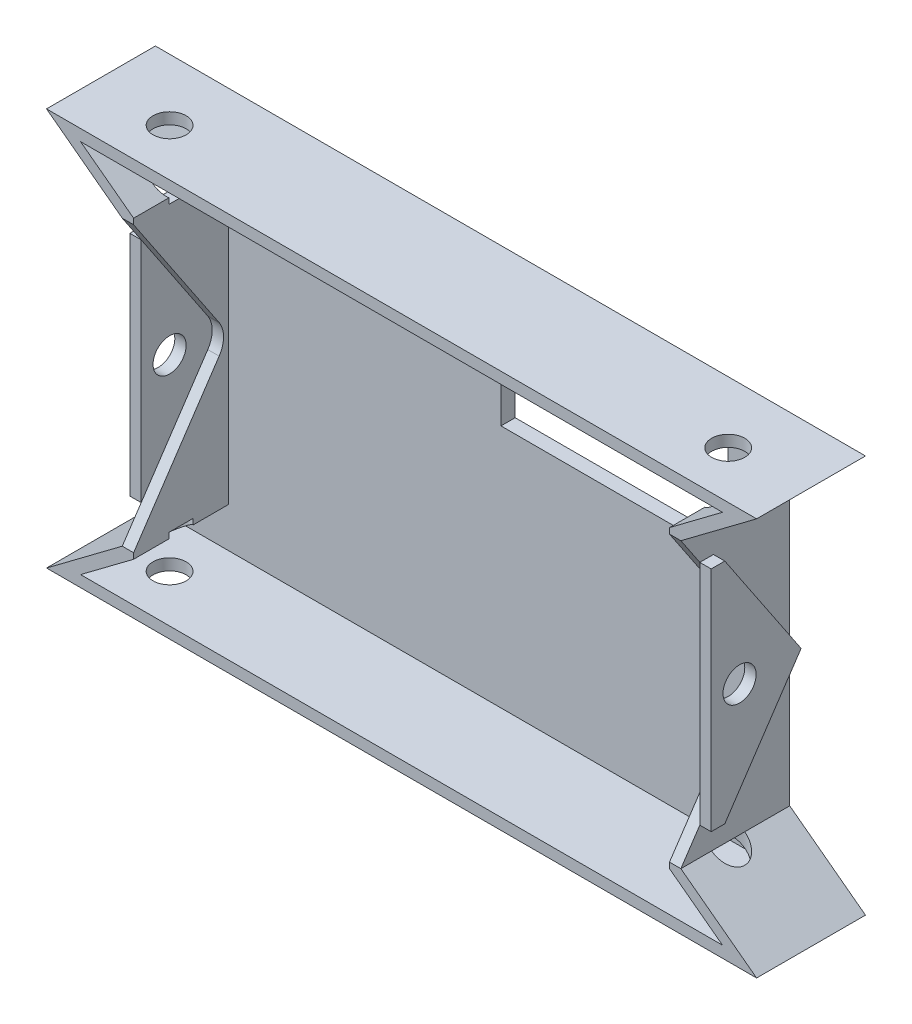
SolidWorks part; units mm, degrees
ref_plane "前视基准面" through (0, 0, 0) normal (0, 0, 1) x (1, 0, 0)
ref_plane "上视基准面" through (0, 0, 0) normal (0, 1, 0) x (1, 0, 0)
ref_plane "右视基准面" through (0, 0, 0) normal (1, 0, 0) x (0, 0, -1)
sketch "草图1" plane through (0, 0, 0) normal (0, 0, 1) x (1, 0, 0)
  line L0 (0, 42) -> (0, 0) construction
  line L5 (29.5, 6) -> (37.5, 0)
  line L6 (37.5, 0) -> (-37.5, 0)
  line L7 (0, 21) -> (25.1808, 21) construction
  line L8 (29.5, 6) -> (29.5, 36)
  line L9 (37.5, 42) -> (-37.5, 42)
  line L10 (29.5, 36) -> (37.5, 42)
  line L11 (-29.5, 36) -> (-37.5, 42)
  line L12 (-29.5, 6) -> (-29.5, 36)
  line L13 (-29.5, 6) -> (-37.5, 0)
  point P2 (29.5, 21)
  point P14 (0, 0)
  point P16 (37.8655, 46.0267)
  point P19 (43.209, 41.009)
  dimension "D1" = 59
  dimension "D2" = 42
  dimension "D3" = 6
  dimension "D4" = 8
extrude "凸台-拉伸1" add sketch "草图1" along normal blind 1.5
sketch "草图2" plane through (0, 0, 1.5) normal (0, 0, 1) x (1, 0, 0)
  line L0 (28.3, 36.6) -> (33.9, 40.8)
  line L1 (33.9, 40.8) -> (-33.9, 40.8)
  line L2 (-33.9, 40.8) -> (-28.3, 36.6)
  line L3 (-28.3, 36.6) -> (-28.3, 5.4)
  line L4 (-28.3, 5.4) -> (-33.9, 1.2)
  line L5 (-33.9, 1.2) -> (33.9, 1.2)
  line L6 (33.9, 1.2) -> (28.3, 5.4)
  line L7 (28.3, 5.4) -> (28.3, 36.6)
  line L8 (29.5, 36) -> (37.5, 42)
  line L9 (37.5, 42) -> (-37.5, 42)
  line L10 (-37.5, 42) -> (-29.5, 36)
  line L11 (-29.5, 36) -> (-29.5, 6)
  line L12 (-29.5, 6) -> (-37.5, 0)
  line L13 (-37.5, 0) -> (37.5, 0)
  line L14 (37.5, 0) -> (29.5, 6)
  line L15 (29.5, 6) -> (29.5, 36)
  line L16 (29.5, 36) -> (37.5, 42)
  line L17 (37.5, 42) -> (-37.5, 42)
  line L18 (-37.5, 42) -> (-29.5, 36)
  line L19 (-29.5, 36) -> (-29.5, 6)
  line L20 (-29.5, 6) -> (-37.5, 0)
  line L21 (-37.5, 0) -> (37.5, 0)
  line L22 (37.5, 0) -> (29.5, 6)
  line L23 (29.5, 6) -> (29.5, 36)
  dimension "D1" = 0
  dimension "D2" = 1.2
extrude "凸台-拉伸2" add sketch "草图2" along normal blind 10
sketch "草图3" plane through (0, 42, 0) normal (0, 1, 0) x (1, 0, 0)
  line L0 (0, 0) -> (0, -11.5) construction
  line L1 (37.5, 0) -> (-37.5, 0) construction
  line L2 (37.5, -11.5) -> (-37.5, -11.5) construction
  circle A0 centre (-29.5, -6.5) radius 1.75
  circle A1 centre (29.5, -6.5) radius 1.75
  dimension "D1" = 3.5
  dimension "D2" = 59
  dimension "D3" = 6.5
extrude "切除-拉伸1" cut sketch "草图3" against normal through all
sketch "草图4" plane through (29.5, 0, 0) normal (1, 0, 0) x (0, 0, -1)
  line L0 (-4.75, 36) -> (-4.75, 6) construction
  line L1 (-2.4662, 22.5319) -> (-11.5, 36)
  line L2 (-2, 21) -> (-17.7429, 21) construction
  line L3 (-2.4662, 19.4681) -> (-11.5, 6)
  line L4 (-11.5, 36) -> (-11.5, 6)
  line L5 (0, 6) -> (0, 36) construction
  arc A0 (-2.4662, 19.4681) -> (-2.4662, 22.5319) centre (-4.75, 21) ccw
  point P1 (-1.9123, 21)
  dimension "D1" = 2
extrude "切除-拉伸2" cut sketch "草图4" against normal through all
sketch "草图5" plane through (29.5, 0, 0) normal (1, 0, 0) x (0, 0, -1)
  line L0 (-4.75, 25.9367) -> (-8.25, 31.1547)
  line L1 (-8.25, 31.1547) -> (-8.25, 36)
  line L2 (-8.25, 36) -> (-4.75, 36)
  line L3 (-4.75, 36) -> (0, 36) construction
  line L4 (-4.75, 16.0633) -> (-8.25, 10.8453)
  line L5 (-8.25, 10.8453) -> (-8.25, 6)
  line L6 (-8.25, 6) -> (-4.75, 6)
  line L7 (-4.75, 6) -> (-4.75, 16.0633)
  line L8 (-4.75, 36) -> (-4.75, 25.9367)
  ellipse E0 centre (-6.5, 36) end of major axis (-8.25, 36) minor radius 1.3125 (-4.75, 36) -> (-8.25, 36) ccw construction
extrude "凸台-拉伸3" add sketch "草图5" against normal blind 1.2
sketch "草图6" plane through (-29.5, 0, 0) normal (-1, 0, 0) x (0, 0, 1)
  line L0 (8.25, 6) -> (4.75, 6)
  line L1 (4.75, 6) -> (4.75, 16.0633)
  line L2 (4.75, 16.0633) -> (8.25, 10.8453)
  line L3 (8.25, 10.8453) -> (8.25, 6)
  line L4 (4.75, 25.9367) -> (8.25, 31.1547)
  line L5 (8.25, 36) -> (8.25, 31.1547) construction
  line L6 (8.25, 31.1547) -> (11.5, 36) construction
  line L7 (8.25, 31.1547) -> (8.25, 36)
  line L8 (8.25, 36) -> (4.75, 36)
  line L9 (4.75, 36) -> (4.75, 25.9367)
extrude "凸台-拉伸4" add sketch "草图6" against normal blind 1.2
sketch "草图7" plane through (-29.5, 0, 0) normal (-1, 0, 0) x (0, 0, 1)
  line L0 (9.5, 21) -> (9.5, 33.0183)
  line L1 (2.4662, 22.5319) -> (11.5, 36) construction
  line L3 (9.5, 21) -> (9.5, 8.9817)
  line L4 (11.5, 6) -> (2.4662, 19.4681) construction
  line L6 (0, 36) -> (0, 6) construction
  line L7 (9.5, 8.9817) -> (8.0613, 8.9817)
  line L8 (8.0613, 8.9817) -> (0, 21)
  line L9 (0, 21) -> (8.0613, 33.0183)
  line L10 (8.0613, 33.0183) -> (9.5, 33.0183)
  line L11 (0, 21) -> (13.4765, 21) construction
  circle A0 centre (4.75, 21) radius 4.75 construction
  circle A4 centre (6.5, 21) radius 1.75
  point P8 (4.75, 21)
  point P19 (5, 21)
  dimension "D1" = 6.5
  dimension "D2" = 3.5
extrude "凸台-拉伸5" add sketch "草图7" along normal blind 1.2
sketch "草图8" plane through (29.5, 0, 0) normal (1, 0, 0) x (0, 0, -1)
  line L0 (-9.5, 8.9817) -> (-9.5, 33.0183)
  line L1 (-9.5, 33.0183) -> (-8.0613, 33.0183)
  line L2 (-8.0613, 33.0183) -> (0, 21)
  line L3 (0, 21) -> (-8.0613, 8.9817)
  line L4 (-8.0613, 8.9817) -> (-9.5, 8.9817)
  circle A2 centre (-6.5, 21) radius 1.75
  circle A3 centre (-6.5, 21) radius 1.75 construction
extrude "凸台-拉伸6" add sketch "草图8" along normal blind 1.2
sketch "草图9" plane through (0, 0, 0) normal (0, 0, -1) x (-1, 0, 0)
  line L0 (-29.5, 21) -> (-29.5, 36) construction
  line L1 (-24.5, 37) -> (-0.5, 37)
  line L2 (-24.5, 37) -> (-24.5, 27)
  line L3 (-24.5, 27) -> (-0.5, 27)
  line L4 (-0.5, 37) -> (-0.5, 27)
  line L5 (-37.5, 42) -> (37.5, 42) construction
  dimension "D1" = 24
  dimension "D2" = 10
  dimension "D3" = 5
  dimension "D4" = 5
extrude "切除-拉伸4" cut sketch "草图9" against normal through all
